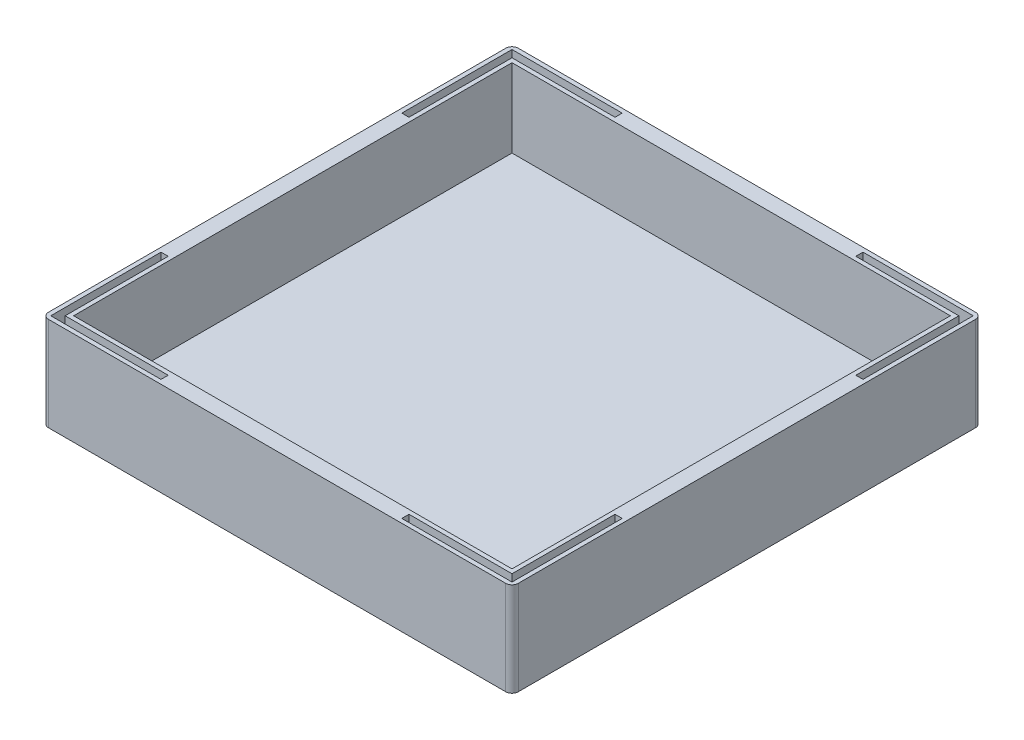
SolidWorks part; units mm, degrees
ref_plane "Front Plane" through (0, 0, 0) normal (0, 0, 1) x (1, 0, 0)
ref_plane "Top Plane" through (0, 0, 0) normal (0, 1, 0) x (1, 0, 0)
ref_plane "Right Plane" through (0, 0, 0) normal (1, 0, 0) x (0, 0, -1)
sketch "Sketch3" plane through (0, 0, 0) normal (0, 1, 0) x (1, 0, 0)
  line L1 (0, 0) -> (150, 0)
  line L2 (0, 0) -> (0, 150)
  line L3 (0, 150) -> (150, 150)
  line L4 (150, 0) -> (150, 150)
  dimension "D1" = 150
  dimension "D2" = 150
extrude "Boss-Extrude1" add sketch "Sketch3" along normal blind 30
shell "Shell1" thickness 5
sketch "Sketch5" plane through (0, 30, 0) normal (0, 1, 0) x (1, 0, 0)
  line L0 (1.35, 148.65) -> (36.55, 148.65)
  line L1 (36.55, 148.65) -> (36.55, 146.35)
  line L2 (36.55, 146.35) -> (3.65, 146.35)
  line L3 (3.65, 146.35) -> (3.65, 113.45)
  line L4 (3.65, 113.45) -> (1.35, 113.45)
  line L5 (1.35, 113.45) -> (1.35, 148.65)
  line L6 (75, 141.0917) -> (75, -18.9083) construction
  line L7 (-34.1594, 75) -> (125.8406, 75) construction
  line L8 (148.65, 113.45) -> (148.65, 148.65)
  line L9 (146.35, 113.45) -> (148.65, 113.45)
  line L10 (146.35, 146.35) -> (146.35, 113.45)
  line L11 (113.45, 146.35) -> (146.35, 146.35)
  line L12 (113.45, 148.65) -> (113.45, 146.35)
  line L13 (148.65, 148.65) -> (113.45, 148.65)
  line L14 (148.65, 1.35) -> (113.45, 1.35)
  line L15 (113.45, 1.35) -> (113.45, 3.65)
  line L16 (113.45, 3.65) -> (146.35, 3.65)
  line L17 (146.35, 3.65) -> (146.35, 36.55)
  line L18 (146.35, 36.55) -> (148.65, 36.55)
  line L19 (148.65, 36.55) -> (148.65, 1.35)
  line L20 (1.35, 36.55) -> (1.35, 1.35)
  line L21 (3.65, 36.55) -> (1.35, 36.55)
  line L22 (3.65, 3.65) -> (3.65, 36.55)
  line L23 (36.55, 3.65) -> (3.65, 3.65)
  line L24 (36.55, 1.35) -> (36.55, 3.65)
  line L25 (1.35, 1.35) -> (36.55, 1.35)
  line L26 (150, 150) -> (0, 150) construction
  line L27 (0, 150) -> (0, 0) construction
  line L30 (150, 0) -> (150, 150) construction
  line L31 (0, 0) -> (150, 0) construction
  dimension "D1" = 2.3
  dimension "D2" = 2.3
  dimension "D3" = 35.2
  dimension "D4" = 35.2
  dimension "D5" = 1.35
  dimension "D6" = 1.35
  dimension "D7" = 1.35
  dimension "D8" = 1.35
  dimension "D9" = 180
extrude "Cut-Extrude1" cut sketch "Sketch5" against normal blind 20
fillet "Fillet2" radius 2 4 edges at (150, 15, -150) (150, 15, 0) (0, 15, 0) (0, 15, -150)
